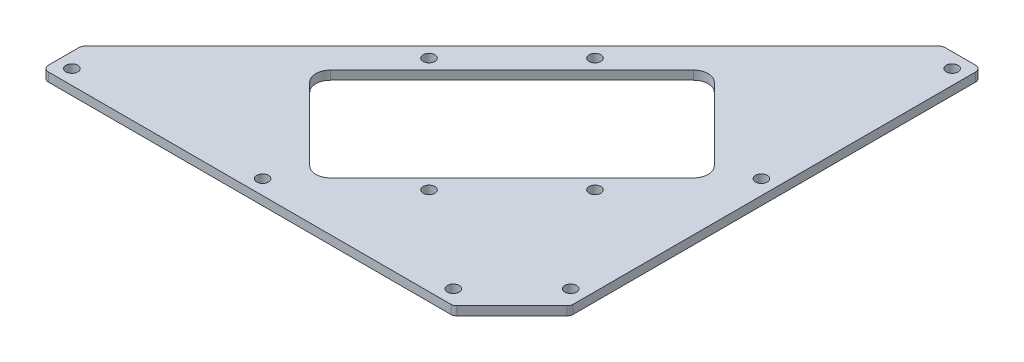
SolidWorks part; units mm, degrees
material "5052-H34"
ref_plane "正面" through (0, 0, 0) normal (0, 0, 1) x (1, 0, 0)
ref_plane "平面" through (0, 0, 0) normal (0, 1, 0) x (1, 0, 0)
ref_plane "右側面" through (0, 0, 0) normal (1, 0, 0) x (0, 0, -1)
sketch "ｽｹｯﾁ1" plane through (0, 0, 0) normal (0, 1, 0) x (1, 0, 0)
  line L0 (0, 20) -> (0, 160)
  line L1 (0, 175) -> (-5, 170) construction
  line L2 (-160, 0) -> (-20, 0)
  line L3 (-5, 0) -> (-5, 76.3173) construction
  line L4 (0, 0) -> (-87.5, 87.5) construction
  line L5 (-20, 0) -> (0, 20)
  line L6 (-82.2012, 13.2583) -> (-13.2583, 82.2012)
  line L7 (-97.2272, 68.9429) -> (-58.3363, 30.052) construction
  line L8 (-97.2272, 68.9429) -> (-68.9429, 97.2272) construction
  line L9 (-58.3363, 30.052) -> (-30.052, 58.3363) construction
  line L10 (-68.9429, 97.2272) -> (-30.052, 58.3363) construction
  line L11 (-97.2272, 68.9429) -> (-30.052, 58.3363) construction
  line L12 (-58.3363, 30.052) -> (-68.9429, 97.2272) construction
  line L13 (-63.6396, 63.6396) -> (-49.4975, 77.7817) construction
  line L14 (-10, 165) -> (-10, 0) construction
  line L15 (-82.2012, 13.2583) -> (-114.021, 45.0781)
  line L16 (-13.2583, 82.2012) -> (-45.0781, 114.021)
  line L17 (-114.021, 45.0781) -> (-45.0781, 114.021)
  line L18 (-82.2012, 13.2583) -> (-45.0781, 114.021) construction
  line L19 (-13.2583, 82.2012) -> (-114.021, 45.0781) construction
  line L20 (-20, 0) -> (-10, 0) construction
  line L21 (-5, 0) -> (0, 0) construction
  line L22 (-10, 0) -> (-5, 0) construction
  line L23 (0, 0) -> (0, 20) construction
  line L24 (-128.1631, 45.0781) -> (-45.0781, 128.1631)
  line L25 (0.8839, 82.2012) -> (0, 83.085) construction
  line L26 (-82.2012, -0.8839) -> (-81.3173, 0) construction
  line L27 (-128.0456, 44.9606) -> (-128.1631, 45.0781)
  line L30 (-45.0781, 128.1631) -> (-13.2412, 160)
  line L32 (0.8839, 82.2012) -> (-45.0781, 128.1631) construction
  line L33 (-5, 88.085) -> (-10, 93.085) construction
  line L34 (0, 83.085) -> (-5, 88.085) construction
  line L35 (0, 81.3173) -> (0.8839, 82.2012) construction
  line L36 (-82.2012, -0.8839) -> (0.8839, 82.2012) construction
  line L37 (-10, 71.3173) -> (-5, 76.3173) construction
  line L38 (-5, 76.3173) -> (0, 81.3173) construction
  line L39 (-5, 76.3173) -> (-5, 88.085) construction
  line L40 (-5, 88.085) -> (-5, 170) construction
  line L41 (-40.6586, 40.6586) -> (-10, 71.3173) construction
  line L42 (-81.3173, 0) -> (-40.6586, 40.6586) construction
  line L43 (-82.2012, -0.8839) -> (-83.085, 0) construction
  line L44 (-82.2012, -0.8839) -> (-128.1631, 45.0781) construction
  line L45 (-83.085, 0) -> (-128.0456, 44.9606) construction
  line L46 (-175, 0) -> (-160, 0) construction
  line L47 (-87.5, 87.5) -> (-175, 0) construction
  line L48 (-10, 165) -> (-87.5, 87.5) construction
  line L49 (-5, 170) -> (-10, 165) construction
  line L50 (0, 160) -> (0, 175)
  line L51 (0, 160) -> (-10, 160)
  line L52 (-13.2412, 160) -> (-10, 160)
  line L53 (-128.1631, 45.0781) -> (-160, 13.2412)
  line L54 (-160, 13.2412) -> (-160, 10)
  line L55 (-160, 0) -> (-160, 10)
  circle A0 centre (-5, 25) radius 2
  circle A1 centre (-5, 90) radius 2
  circle A2 centre (-90, 5) radius 2
  circle A3 centre (-25, 5) radius 2
  circle A4 centre (-68.9429, 97.2272) radius 2
  circle A5 centre (-30.052, 58.3363) radius 2
  circle A6 centre (-58.3363, 30.052) radius 2
  circle A7 centre (-97.2272, 68.9429) radius 2
  circle A8 centre (-5, 155) radius 2
  circle A9 centre (-155, 5) radius 2
  point P20 (-63.6396, 63.6396)
  dimension "D3" = 4
  dimension "D9" = 4
  dimension "D1" = 5
  dimension "D2" = 170
  dimension "D4" = 25
  dimension "D5" = 65
  dimension "D6" = 65
  dimension "D7" = 40
  dimension "D8" = 55
  dimension "D10" = 10
  dimension "D11" = 90
  dimension "D12" = 20
  dimension "D13" = 45
  dimension "D14" = 97.5
  dimension "D16" = 5
  dimension "D15" = 10
extrude "ﾎﾞｽ - 押し出し1" add sketch "ｽｹｯﾁ1" along normal blind 3
sketch "ｽｹｯﾁ3" plane through (0, 3, 0) normal (0, 1, 0) x (1, 0, 0)
  line L0 (-86.6206, 86.6206) -> (-10, 10) construction
  line L1 (-58.3363, 30.052) -> (-30.052, 58.3363) construction
  line L2 (-40.6586, 47.7297) -> (-6.4645, 13.5355) construction
  line L3 (-32.4004, 39.4715) -> (-14.7227, 21.7938) construction
  line L4 (-30.6326, 41.2392) -> (-12.955, 23.5616)
  line L5 (-34.1682, 37.7037) -> (-16.4905, 20.026)
  line L6 (-13.2412, 160) -> (-160, 13.2412)
  line L7 (-160, 13.2412) -> (-160, 0)
  line L8 (-160, 0) -> (-20, 0)
  line L9 (-20, 0) -> (0, 20)
  line L10 (0, 20) -> (0, 160)
  line L11 (0, 160) -> (-13.2412, 160)
  line L12 (-13.2412, 160) -> (-160, 13.2412)
  line L13 (-160, 13.2412) -> (-160, 0)
  line L14 (-160, 0) -> (-20, 0)
  line L15 (-20, 0) -> (0, 20)
  line L16 (0, 20) -> (0, 160)
  line L17 (0, 160) -> (-13.2412, 160)
  line L18 (-32.4004, 39.4715) -> (0, 71.8718) construction
  line L19 (-25.3293, 46.5425) -> (-14.7227, 35.9359) construction
  line L20 (-23.5616, 48.3103) -> (-12.955, 37.7037)
  line L21 (-27.0971, 44.7748) -> (-16.4905, 34.1682)
  line L22 (-18.2583, 53.6136) -> (-12.955, 48.3103) construction
  line L23 (-16.4905, 55.3814) -> (-11.1872, 50.0781)
  line L24 (-20.026, 51.8458) -> (-14.7227, 46.5425)
  line L25 (-39.4715, 32.4004) -> (-21.7938, 14.7227) construction
  line L26 (-41.2392, 30.6326) -> (-23.5616, 12.955)
  line L27 (-37.7037, 34.1682) -> (-20.026, 16.4905)
  line L28 (-46.5425, 25.3293) -> (-35.9359, 14.7227) construction
  line L29 (-48.3103, 23.5616) -> (-37.7037, 12.955)
  line L30 (-44.7748, 27.0971) -> (-34.1682, 16.4905)
  line L31 (-53.6136, 18.2583) -> (-48.3103, 12.955) construction
  line L32 (-55.3814, 16.4905) -> (-50.0781, 11.1872)
  line L33 (-51.8458, 20.026) -> (-46.5425, 14.7227)
  arc A0 (-30.6326, 41.2392) -> (-34.1682, 37.7037) centre (-32.4004, 39.4715) ccw
  arc A1 (-16.4905, 20.026) -> (-12.955, 23.5616) centre (-14.7227, 21.7938) ccw
  arc A2 (-23.5616, 48.3103) -> (-27.0971, 44.7748) centre (-25.3293, 46.5425) ccw
  arc A3 (-16.4905, 34.1682) -> (-12.955, 37.7037) centre (-14.7227, 35.9359) ccw
  arc A4 (-16.4905, 55.3814) -> (-20.026, 51.8458) centre (-18.2583, 53.6136) ccw
  arc A5 (-14.7227, 46.5425) -> (-11.1872, 50.0781) centre (-12.955, 48.3103) ccw
  arc A6 (-41.2392, 30.6326) -> (-37.7037, 34.1682) centre (-39.4715, 32.4004) cw
  arc A7 (-20.026, 16.4905) -> (-23.5616, 12.955) centre (-21.7938, 14.7227) cw
  arc A8 (-48.3103, 23.5616) -> (-44.7748, 27.0971) centre (-46.5425, 25.3293) cw
  arc A9 (-34.1682, 16.4905) -> (-37.7037, 12.955) centre (-35.9359, 14.7227) cw
  arc A10 (-55.3814, 16.4905) -> (-51.8458, 20.026) centre (-53.6136, 18.2583) cw
  arc A11 (-46.5425, 14.7227) -> (-50.0781, 11.1872) centre (-48.3103, 12.955) cw
  point P16 (-23.5616, 30.6326)
  point P25 (-20.026, 41.2392)
  point P32 (-15.6066, 50.9619)
  point P39 (-30.6326, 23.5616)
  point P46 (-41.2392, 20.026)
  point P53 (-50.9619, 15.6066)
  dimension "D2" = 5
  dimension "D3" = 5
  dimension "D4" = 25
  dimension "D5" = 10
  dimension "D6" = 15
  dimension "D7" = 7.5
  dimension "D8" = 10
  dimension "D1" = 0
extrude "ｶｯﾄ - 押し出し2" [suppressed] cut sketch "ｽｹｯﾁ3" against normal through all contours A11 L33 A10 L32 | A9 L30 A8 L29 | A7 L27 A6 L26 | L5 A1 L4 A0 | L21 A3 L20 A2 | L24 A5 L23 A4
fillet "ﾌｨﾚｯﾄ1" radius 2 6 edges at (0, 1.5, -20) (-20, 1.5, 0) (-13.2412, 1.5, -160) (0, 1.5, -160) (-160, 1.5, 0) (-160, 1.5, -13.2412)
fillet "ﾌｨﾚｯﾄ2" radius 5 4 edges at (-114.021, 1.5, -45.0781) (-82.2012, 1.5, -13.2583) (-13.2583, 1.5, -82.2012) (-45.0781, 1.5, -114.021)
